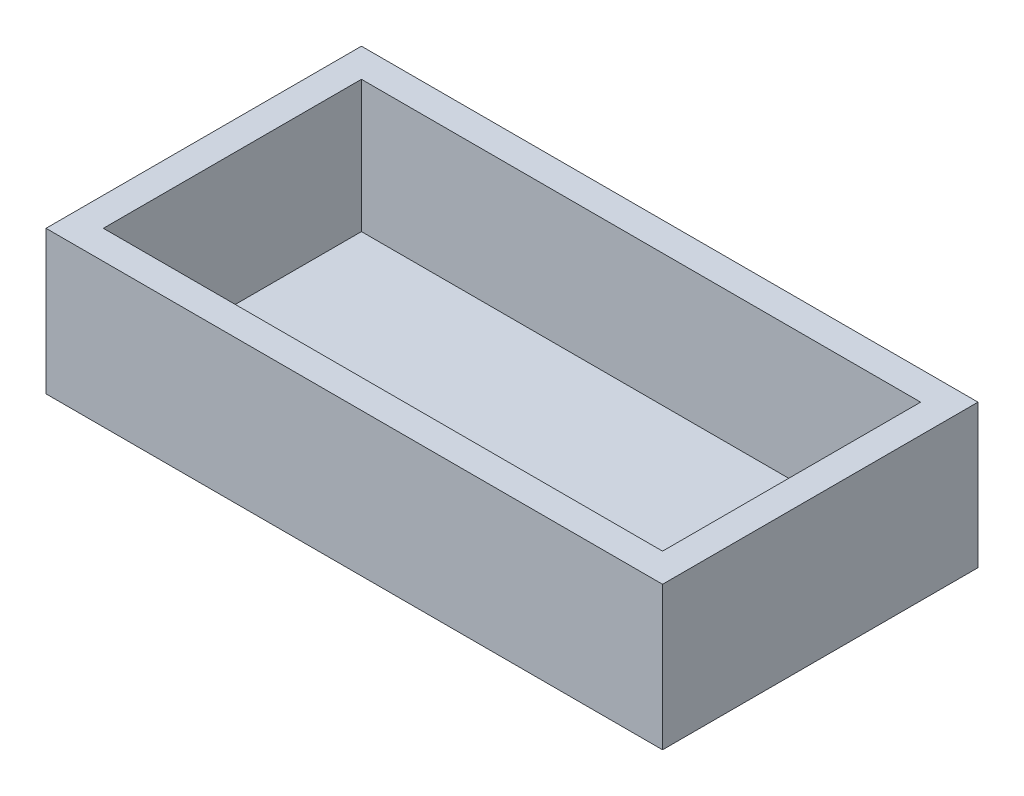
SolidWorks part; units mm, degrees
ref_plane "Спереди" through (0, 0, 0) normal (0, 0, 1) x (1, 0, 0)
ref_plane "Сверху" through (0, 0, 0) normal (0, 1, 0) x (1, 0, 0)
ref_plane "Справа" through (0, 0, 0) normal (1, 0, 0) x (0, 0, -1)
sketch "Эскиз1" plane through (0, 0, 0) normal (0, 1, 0) x (1, 0, 0)
  line L1 (-21.5, -11) -> (21.5, -11)
  line L2 (-21.5, -11) -> (-21.5, 11)
  line L3 (-21.5, 11) -> (21.5, 11)
  line L4 (21.5, -11) -> (21.5, 11)
  line L5 (-21.5, -11) -> (21.5, 11) construction
  line L6 (-21.5, 11) -> (21.5, -11) construction
  point P0 (0, 0)
  dimension "D1" = 43
  dimension "D2" = 22
extrude "Бобышка-Вытянуть2" add sketch "Эскиз1" along normal blind 10
sketch "Эскиз3" plane through (0, 10, 0) normal (0, 1, 0) x (1, 0, 0)
  line L0 (-21.5, 11) -> (-21.5, -11) construction
  line L1 (-19.5, -9) -> (19.5, -9)
  line L2 (-19.5, -9) -> (-19.5, 9)
  line L3 (-19.5, 9) -> (19.5, 9)
  line L4 (19.5, -9) -> (19.5, 9)
  line L5 (-19.5, -9) -> (19.5, 9) construction
  line L6 (-19.5, 9) -> (19.5, -9) construction
  line L7 (21.5, 11) -> (-21.5, 11) construction
  point P0 (0, 0)
  dimension "D1" = 2
  dimension "D2" = 2
extrude "Вырез-Вытянуть1" cut sketch "Эскиз3" against normal blind 9.2
sketch "Эскиз4" plane through (0, 0, -11) normal (0, 0, -1) x (-1, 0, 0)
  line L0 (-21.5, 10) -> (-21.5, 0) construction
  line L1 (-19.5, 3.6) -> (-16.3, 3.6)
  line L2 (-19.5, 3.6) -> (-19.5, 2)
  line L3 (-19.5, 2) -> (-16.3, 2)
  line L4 (-16.3, 3.6) -> (-16.3, 2)
  line L5 (-19.5, 3.6) -> (-16.3, 2) construction
  line L6 (-19.5, 2) -> (-16.3, 3.6) construction
  line L7 (-21.5, 0) -> (21.5, 0) construction
  point P0 (-17.9, 2.8)
  dimension "D1" = 2
  dimension "D2" = 2
  dimension "D3" = 1.6
  dimension "D4" = 3.2
extrude "Вырез-Вытянуть2" cut sketch "Эскиз4" against normal up to surface (2 mm away) up to face at (0, 5.4, -9)
